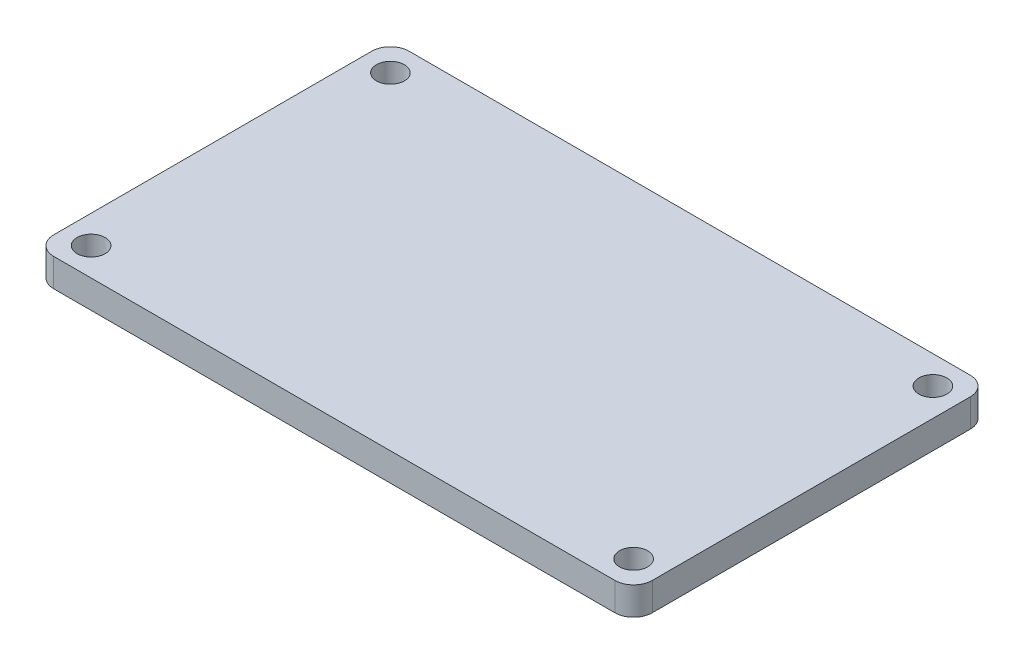
SolidWorks part; units mm, degrees
ref_plane "Front Plane" through (0, 0, 0) normal (0, 0, 1) x (1, 0, 0)
ref_plane "Top Plane" through (0, 0, 0) normal (0, 1, 0) x (1, 0, 0)
ref_plane "Right Plane" through (0, 0, 0) normal (1, 0, 0) x (0, 0, -1)
sketch "Sketch1" plane through (0, 0, 0) normal (0, 1, 0) x (1, 0, 0)
  line L0 (-29, 16) -> (29, 16)
  line L1 (-30, -19) -> (30, -19)
  line L2 (-32, -17) -> (-32, 17)
  line L3 (-30, 19) -> (30, 19)
  line L4 (32, -17) -> (32, 17)
  line L5 (-32, -19) -> (32, 19) construction
  line L6 (-32, 19) -> (32, -19) construction
  line L7 (29, -16) -> (29, 16)
  line L8 (-29, -16) -> (29, -16)
  line L9 (-29, -16) -> (-29, 16)
  line L10 (32, -19) -> (32, 19) construction
  line L11 (-32, 19) -> (32, 19) construction
  line L12 (-32, -19) -> (32, -19) construction
  line L13 (-32, -19) -> (-32, 19) construction
  line L14 (-29, 0) -> (29, 0) construction
  line L15 (0, 16) -> (0, -16) construction
  line L16 (-25, -9) -> (-25, 9)
  line L17 (25, -9) -> (25, 9)
  circle A0 centre (-29, 16) radius 1.5
  circle A1 centre (29, 16) radius 1.5
  circle A2 centre (-29, -16) radius 1.5
  circle A3 centre (29, -16) radius 1.5
  arc A4 (32, 17) -> (30, 19) centre (30, 17) ccw
  arc A5 (32, -17) -> (30, -19) centre (30, -17) cw
  arc A6 (-32, -17) -> (-30, -19) centre (-30, -17) ccw
  arc A7 (-32, 17) -> (-30, 19) centre (-30, 17) cw
  circle A8 centre (-25, 9) radius 1
  circle A9 centre (-25, -9) radius 1
  circle A10 centre (25, -9) radius 1
  circle A11 centre (25, 9) radius 1
  point P0 (0, 0)
  point P33 (-25, 0)
  point P39 (25, 0)
  dimension "D4" = 3
  dimension "D5" = 3
  dimension "D6" = 3
  dimension "D7" = 3
  dimension "D8" = 2
  dimension "D9" = 2
  dimension "D10" = 2
  dimension "D1" = 64
  dimension "D2" = 38
  dimension "D11" = 18
  dimension "D12" = 7
  dimension "D3" = 3
extrude "Boss-Extrude1" add sketch "Sketch1" along normal blind 3
